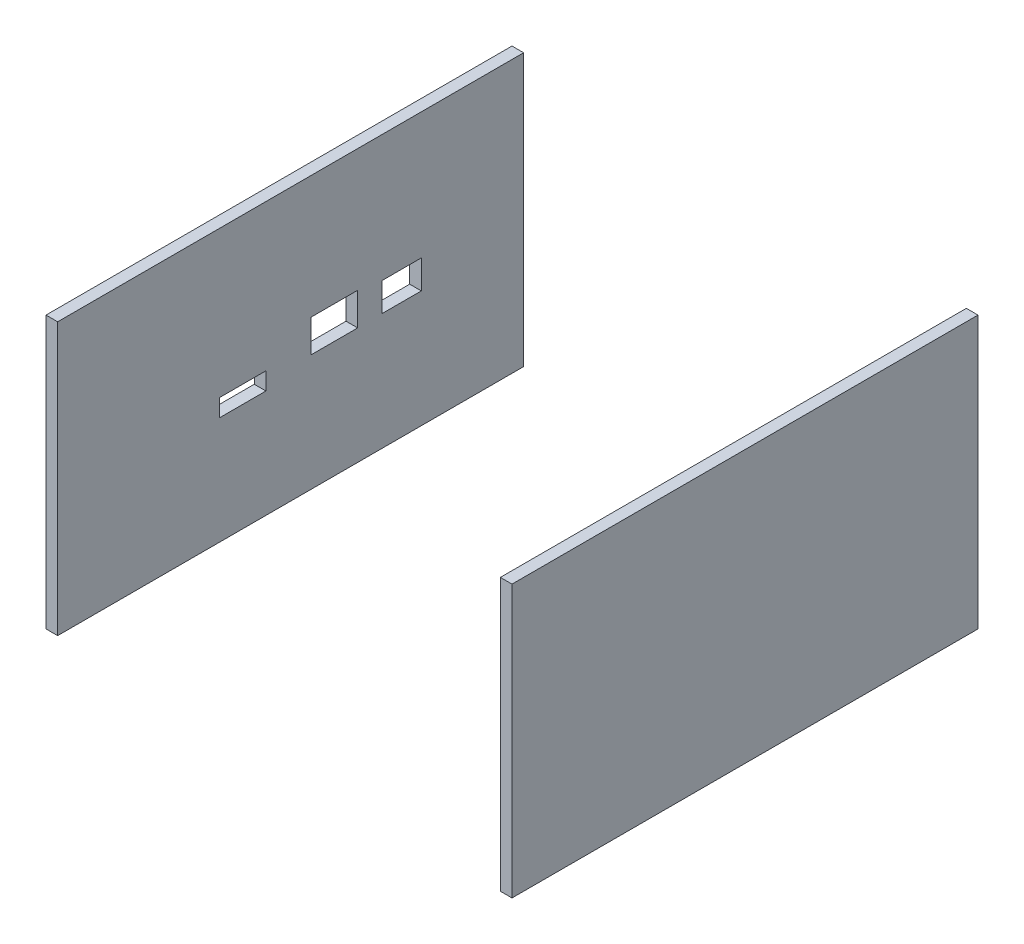
SolidWorks part; units mm, degrees
ref_plane "Front Plane" through (0, 0, 0) normal (0, 0, 1) x (1, 0, 0)
ref_plane "Top Plane" through (0, 0, 0) normal (0, 1, 0) x (1, 0, 0)
ref_plane "Right Plane" through (0, 0, 0) normal (1, 0, 0) x (0, 0, -1)
sketch "Sketch1" plane through (0, 0, 0) normal (0, 1, 0) x (1, 0, 0)
  line L1 (-70, -80) -> (70, -80)
  line L2 (-70, -80) -> (-70, 80)
  line L3 (-70, 80) -> (70, 80)
  line L4 (70, -80) -> (70, 80)
  line L5 (-70, -80) -> (70, 80) construction
  line L6 (-70, 80) -> (70, -80) construction
  point P0 (0, 0)
  dimension "D1" = 140
  dimension "D2" = 160
extrude "Boss-Extrude1" add sketch "Sketch1" along normal blind 3
sketch "Sketch2" plane through (0, 3, 0) normal (0, 1, 0) x (1, 0, 0)
  line L1 (-57, -57) -> (57, -57)
  line L2 (-57, -57) -> (-57, 57)
  line L3 (-57, 57) -> (57, 57)
  line L4 (57, -57) -> (57, 57)
  line L5 (-57, -57) -> (57, 57) construction
  line L6 (-57, 57) -> (57, -57) construction
  line L7 (60, -60) -> (-60, -60)
  line L8 (60, -60) -> (60, 60)
  line L9 (60, 60) -> (-60, 60)
  line L10 (-60, -60) -> (-60, 60)
  line L11 (60, -60) -> (-60, 60) construction
  line L12 (60, 60) -> (-60, -60) construction
  point P0 (0, 0)
  point P6 (0, 0)
  dimension "D1" = 114
  dimension "D2" = 114
  dimension "D3" = 120
extrude "Boss-Extrude2" add sketch "Sketch2" along normal blind 70
sketch "Sketch4" plane through (0, 73, 0) normal (0, 1, 0) x (1, 0, 0)
  line L1 (-60, 60) -> (60, 60)
  line L2 (-60, 60) -> (-60, -60)
  line L3 (-60, -60) -> (60, -60)
  line L4 (60, 60) -> (60, -60)
  dimension "D1" = 120
  dimension "D2" = 120
extrude "Boss-Extrude4" add sketch "Sketch4" along normal blind 3
sketch "Sketch5" plane through (0, 76, 0) normal (0, 1, 0) x (1, 0, 0)
  line L0 (-60, 60) -> (60, -60) construction
  line L1 (-10.27, -9.855) -> (29.63, -9.855)
  line L2 (-10.27, -9.855) -> (-10.27, 9.855)
  line L3 (-10.27, 9.855) -> (29.63, 9.855)
  line L4 (29.63, -9.855) -> (29.63, 9.855)
  line L5 (-10.27, -9.855) -> (29.63, 9.855) construction
  line L6 (-10.27, 9.855) -> (29.63, -9.855) construction
  line L7 (60, -60) -> (60, 60) construction
  line L8 (60, -60) -> (60, 60) construction
  line L9 (60, -60) -> (60, 60) construction
  line L10 (60, 60) -> (-60, 60) construction
  line L11 (60, 60) -> (-60, -60) construction
  circle A1 centre (34.39, -4.925) radius 2.1
  circle A2 centre (34.39, 4.925) radius 2.1
  circle A4 centre (-15.03, -4.925) radius 2.1
  circle A5 centre (-15.03, 4.925) radius 2.1
  point P3 (9.68, 0)
  dimension "D2" = 4.2
  dimension "D6" = 9.85
  dimension "D7" = 4.93
  dimension "D8" = 4.93
  dimension "D9" = 4.93
  dimension "D10" = 9.68
  dimension "D11" = 4.93
  dimension "D12" = 4.93
  dimension "D1" = 39.9
  dimension "D3" = 19.71
  dimension "D4" = 4.76
  dimension "D5" = 4.76
extrude "Cut-Extrude2" cut sketch "Sketch5" against normal blind 3
sketch "Sketch6" plane through (0, 76, 0) normal (0, 1, 0) x (1, 0, 0)
  line L1 (9.1491, -8.655) -> (-9.1491, -8.655)
  line L2 (9.1491, -8.655) -> (9.1491, 8.655)
  line L3 (9.1491, 8.655) -> (-9.1491, 8.655)
  line L4 (-9.1491, -8.655) -> (-9.1491, 8.655)
  line L5 (9.1491, -8.655) -> (-9.1491, 8.655) construction
  line L6 (9.1491, 8.655) -> (-9.1491, -8.655) construction
  point P0 (0, 0)
extrude "Cut-Extrude3" cut sketch "Sketch6" against normal blind 3
sketch "Sketch7" plane through (0, 0, 0) normal (0, 1, 0) x (1, 0, 0)
  line L1 (-45, -45) -> (45, -45)
  line L2 (-45, -45) -> (-45, 45)
  line L3 (-45, 45) -> (45, 45)
  line L4 (45, -45) -> (45, 45)
  line L5 (-45, -45) -> (45, 45) construction
  line L6 (-45, 45) -> (45, -45) construction
  point P0 (0, 0)
  dimension "D1" = 90
  dimension "D2" = 90
sketch "Sketch13" plane through (0, 76, 0) normal (0, 1, 0) x (1, 0, 0)
  arc A0 (-3.7926, 43.0768) -> (-0.8101, -42.9734) centre (-3.7926, 0) ccw construction
  arc A1 (-3.7926, 49.7288) -> (-0.3495, -49.6094) centre (-3.7926, 0) ccw
  arc A2 (-3.7926, 36.4249) -> (-1.2706, -36.3375) centre (-3.7926, 0) ccw
  arc A3 (-3.7926, 36.4249) -> (-3.7926, 49.7288) centre (-3.7926, 43.0768) ccw
  arc A4 (-0.3495, -49.6094) -> (-1.2706, -36.3375) centre (-0.8101, -42.9734) ccw
  point P3 (-46.8436, -1.4922)
extrude "Cut-Extrude8" cut sketch "Sketch13" against normal blind 5
sketch "Sketch15" plane through (0, 3, 0) normal (0, 1, 0) x (1, 0, 0)
  line L0 (70, 80) -> (-70, 80) construction
  line L1 (90, 80) -> (-169.0216, 80)
  line L2 (90, 80) -> (90, -100.2694)
  line L3 (90, -100.2694) -> (-169.0216, -100.2694)
  line L4 (-169.0216, 80) -> (-169.0216, -100.2694)
extrude "Boss-Extrude5" add sketch "Sketch15" against normal blind 3
sketch "Sketch18" plane through (0, 3, 0) normal (0, 1, 0) x (1, 0, 0)
  circle A0 centre (-55.452, -27.2274) radius 1.6 construction
  circle A1 centre (-55.452, -27.2274) radius 1.6
  circle A2 centre (-55.452, 32.2086) radius 1.6 construction
  circle A3 centre (-55.452, 32.2086) radius 1.6
  circle A4 centre (4.746, 32.2086) radius 1.6 construction
  circle A5 centre (4.746, 32.2086) radius 1.6
  circle A6 centre (4.746, -27.2274) radius 1.6 construction
  circle A7 centre (4.746, -27.2274) radius 1.6
extrude "Cut-Extrude9" cut sketch "Sketch18" against normal blind 10
sketch "Sketch19" plane through (-60, 0, 0) normal (-1, 0, 0) x (0, 0, 1)
  line L0 (12.3674, 3) -> (12.3674, 33) construction
  line L1 (-60, 3) -> (60, 3) construction
  line L2 (-5.6466, 31.35) -> (-5.6466, 26.9) construction
  line L3 (6.3674, 30.75) -> (18.3674, 30.75)
  line L4 (6.3674, 30.75) -> (6.3674, 35.25)
  line L5 (6.3674, 35.25) -> (18.3674, 35.25)
  line L6 (18.3674, 30.75) -> (18.3674, 35.25)
  line L7 (6.3674, 30.75) -> (18.3674, 35.25) construction
  line L8 (6.3674, 35.25) -> (18.3674, 30.75) construction
  line L9 (-5.2594, 33) -> (-5.2594, 41.4) construction
  line L10 (-5.2594, 33) -> (-17.2594, 33) construction
  line L11 (-5.2594, 41.4) -> (-17.2594, 41.4) construction
  line L12 (-17.2594, 33) -> (-17.2594, 41.4) construction
  line L13 (-33.6488, 33.0619) -> (-23.5648, 33.0619) construction
  line L14 (-28.1126, 38.85) -> (-28.1126, 27.45) construction
  line L15 (-23.5648, 40.424) -> (-23.5648, 33.0619) construction
  line L16 (-33.6488, 40.424) -> (-23.5648, 40.424) construction
  line L17 (-33.6488, 40.424) -> (-33.6488, 33.0619) construction
  line L18 (-5.2594, 33) -> (-5.2594, 41.4)
  line L19 (-5.2594, 33) -> (-17.2594, 33)
  line L20 (-5.2594, 41.4) -> (-17.2594, 41.4)
  line L21 (-17.2594, 33) -> (-17.2594, 41.4)
  line L22 (-33.6488, 33.0619) -> (-23.5648, 33.0619)
  line L23 (-28.1126, 38.85) -> (-28.1126, 27.45)
  line L24 (-23.5648, 40.424) -> (-23.5648, 33.0619)
  line L25 (-33.6488, 40.424) -> (-23.5648, 40.424)
  line L26 (-33.6488, 40.424) -> (-33.6488, 33.0619)
  dimension "D1" = 14.86
  dimension "D2" = 30
  dimension "D3" = 4.5
  dimension "D4" = 90
  dimension "D5" = 12
extrude "Cut-Extrude11" cut sketch "Sketch19" against normal blind 5
sketch "Sketch20" plane through (0, 0, 60) normal (0, 0, 1) x (1, 0, 0)
  line L0 (60, 76) -> (60, 3) construction
  line L1 (-169.0216, 3) -> (94.8999, 3)
  line L2 (-169.0216, 3) -> (-169.0216, -16.6306)
  line L3 (-169.0216, -16.6306) -> (94.8999, -16.6306)
  line L4 (94.8999, 3) -> (94.8999, -16.6306)
  line L5 (-60, 76) -> (60, 76)
  line L6 (-60, 76) -> (-60, 73)
  line L7 (-60, 73) -> (60, 73)
  line L8 (60, 76) -> (60, 73)
  dimension "D1" = 3
extrude "Cut-Extrude12" cut sketch "Sketch20" against normal through all
sketch "Sketch21" plane through (0, 3, 0) normal (0, 1, 0) x (1, 0, 0)
  line L1 (-169.0216, -60) -> (90, -60)
  line L2 (-169.0216, -60) -> (-169.0216, -100.2694)
  line L3 (-169.0216, -100.2694) -> (90, -100.2694)
  line L4 (90, -60) -> (90, -100.2694)
extrude "Cut-Extrude13" cut sketch "Sketch21" against normal through all
sketch "Sketch22" plane through (0, 73, 0) normal (0, 1, 0) x (1, 0, 0)
  line L0 (-60, 60) -> (60, 60) construction
  line L1 (-57, 60) -> (57, 60)
  line L2 (-57, 60) -> (-57, -65.7824)
  line L3 (-57, -65.7824) -> (57, -65.7824)
  line L4 (57, 60) -> (57, -65.7824)
  line L5 (-60, 60) -> (-60, -60) construction
  line L6 (60, 60) -> (60, -60) construction
  dimension "D1" = 3
  dimension "D2" = 3
extrude "Cut-Extrude14" cut sketch "Sketch22" against normal through all
